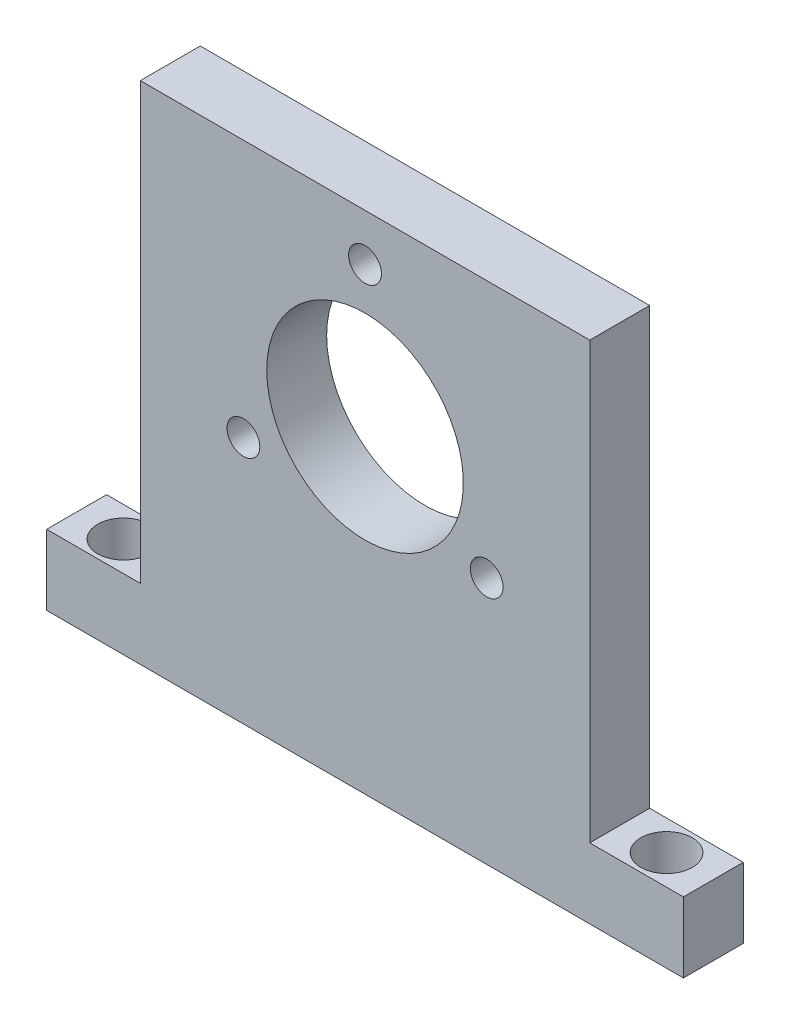
SolidWorks part; units mm, degrees
material "1060 Alloy"
ref_plane "Frontal Plane" through (0, 0, 0) normal (0, 0, 1) x (1, 0, 0)
ref_plane "Horizontal Plane" through (0, 0, 0) normal (0, 1, 0) x (1, 0, 0)
ref_plane "Profile Plane" through (0, 0, 0) normal (1, 0, 0) x (0, 0, -1)
sketch "Sketch2" plane through (0, 0, 0) normal (0, 0, 1) x (1, 0, 0)
  line L0 (-34, 0) -> (34, 0)
  line L1 (34, 0) -> (34, 7.5)
  line L2 (34, 7.5) -> (24, 7.5)
  line L3 (24, 7.5) -> (24, 54)
  line L4 (24, 54) -> (-24, 54)
  line L5 (-24, 54) -> (-24, 7.5)
  line L6 (-24, 7.5) -> (-34, 7.5)
  line L7 (-34, 7.5) -> (-34, 0)
  circle A0 centre (0, 34) radius 4.175
  point P4 (0, 0)
  point P11 (0, 54)
  dimension "D2" = 8.35
  dimension "D1" = 48
  dimension "D3" = 7.5
  dimension "D5" = 34
  dimension "D4" = 10
  dimension "D6" = 20
extrude "Boss-Extrude1" add sketch "Sketch2" against normal blind 6.4
ref_plane "Plane1" through (0, 0, -6.4) normal (0, 0, -1) x (-1, 0, 0)
sketch "Sketch3" plane through (0, 0, -6.4) normal (0, 0, -1) x (-1, 0, 0)
  circle A0 centre (0, 34) radius 10.5
  dimension "D1" = 21
extrude "Cut-Extrude1" cut sketch "Sketch3" against normal through all
sketch "Sketch4" plane through (0, 0, 0) normal (0, 0, 1) x (1, 0, 0)
  circle A0 centre (0, 34) radius 15 construction
  circle A1 centre (0, 34) radius 10.5 construction
  point P4 (0, 49)
  dimension "D1" = 30
hole_wizard "Ø3.5 (3.5) Diameter Hole1" positions "Sketch4" profile "Sketch5" hole size "Ø3.5" standard "ANSI Metric" end condition up to next
sketch "Sketch5" plane through (0, 49, 0) normal (1, 0, 0) x (0, -1, 0)
  line L0 (0, 0) -> (0, 6.4)
  line L1 (0, 6.4) -> (1.75, 6.4)
  line L2 (1.75, 6.4) -> (1.75, 0)
  line L5 (1.75, 0) -> (0, 0)
  line L11 (0, -6.35) -> (0, 107.95) construction
  dimension "Thru Hole Dia." = 3.5
  dimension "Thru Hole Depth" = 6.4
pattern_circular "CirPattern1" count 3 over 360 about axis through (0, 34, 0) along (0, 0, 1) of "Ø3.5 (3.5) Diameter Hole1"
sketch "Sketch12" plane through (0, 7.5, 0) normal (0, 1, 0) x (1, 0, 0)
  line L0 (-34, 6.4) -> (-34, 0) construction
  line L1 (-24, 6.4) -> (-24, 0) construction
  line L2 (24, 6.4) -> (24, 0) construction
  circle A0 centre (-29, 3.2) radius 2.75
  circle A1 centre (29, 3.2) radius 2.75
  point P7 (-34, 3.2)
  dimension "D1" = 5.5
  dimension "D2" = 5
  dimension "D3" = 5
extrude "Cut-Extrude2" cut sketch "Sketch12" along normal through all and the other way through all
equation "\"D1@Sketch2\"=\"EncoderRadius\"*2+1cm"
equation "\"D2@Sketch2\" = \"ActuatorPinD\" + 2mm"
equation "\"D3@Sketch2\"= \"EncoderHousingThickness\""
equation "\"D5@Sketch2\"=\"PillowBlockCenterH\""
equation "\"PinDiameter\"= 0"
equation "\"WallThickness\"= 0.5cm"
equation "\"BottomPlateX\"= 3ft"
equation "\"ActuatorL\"= 35cm"
equation "\"ActuatorPinD\"= 6.35mm"
equation "\"ActuatorPinL\"= 15cm"
equation "\"Box-X\"= 40cm"
equation "\"Box-Z\"= 20cm"
equation "\"Box-Y\"= 30cm"
equation "\"RotaryUnionThickness\"= 1cm"
equation "\"ArmPlateThickness\"= .125in"
equation "\"ArmPlateX\"= 18in"
equation "\"Arm1X\"= 5cm"
equation "\"Arm1L\"= 60cm"
equation "\"Arm2GAP\"= 5cm"
equation "\"Arm2L\"= 60cm"
equation "\"Arm2H\"= 5cm"
equation "\"Arm2Extension\"= 5cm"
equation "\"Arm3GAP\"= 5cm"
equation "\"Arm3L\"= 60cm"
equation "\"Arm3H\"= 5cm"
equation "\"Pin1-2L\"= \"Arm2GAP\" + (2 * \"WallThickness\")"
equation "\"Pin2-3L\"= \"Arm3GAP\" + (4 * \"WallThickness\")"
equation "\"DCMotor1D\"= 65mm"
equation "\"DCMotor1L\"= 215mm"
equation "\"DCMotor1ShaftL\"= 30mm"
equation "\"DCMotor2X\"= 68mm"
equation "\"DCMotor2D\"= 65mm"
equation "\"DCMotor2L\"= 208mm"
equation "\"DCMotor2ShaftL\"= 39mm"
equation "\"DCMotor2ShaftD\"= 15mm"
equation "\"BenchDepth\"= 5cm"
equation "\"BenchH\"= 10cm"
equation "\"BenchL\"= 15cm"
equation "\"PillowBlockW\"= 5cm"
equation "\"PillowBlockCenterH\"= \"DCMotor2X\"/2"
equation "\"EncoderRadius\"= 19mm"
equation "\"EncoderShaftL\"= 15mm"
equation "\"EncoderL\"= 33mm"
equation "\"EncoderHousingThickness\"= 7.5mm"
equation "\"PillowBlockCenterH\"= \"EncoderRadius\" + 5mm"
equation "\"RodRadius\"= .5cm"
equation "\"RodL\"= 20cm"
equation "\"PendulumShaftRadius\"= 4mm"
equation "\"PendulumShaftL\"= \"SlidePlateW\""
equation "\"EncoderShaftRadius\"= 3mm"
equation "\"BeltLockH\"= \"PulleyH\" + 11.885mm - (\"SlidePlateThickness\" + \"SlidePlateClearance\" + 15mm + 5mm)"
equation "\"BeltW\"= .375in"
equation "\"BeltThickness\"= 2mm"
equation "\"BeltL\"= 1500mm + \"BoxX\""
equation "\"HeadstoneThickness\"= 7.5mm"
equation "\"MotorShaftL\"= 18mm"
equation "\"MotorShaftRadius\"= 2.5mm"
equation "\"MotorRadius\"= 21mm"
equation "\"MotorL\"= 83mm"
equation "\"PulleyShaft2L\"= \"BoxX\"+ 3mm"
equation "\"PulleyShaftL\"= \"BoxX\" + 5cm"
equation "\"PulleyShaftDiameter\"= 8mm"
equation "\"PulleyH\"= 2cm + \"SlidePlateClearance\" + (\"SlidePlateThickness\"/2)"
equation "\"PulleyRadius\"= 15.1mm"
equation "\"BoxH\"= 2cm + \"SlidePlateClearance\" + \"SlidePlateThickness\" + 3cm"
equation "\"BoxX\"= \"RailGap\" + 30mm"
equation "\"BoxThickness\"= .5cm"
equation "\"SlidePlateClearance\"= 1cm"
equation "\"SlidePlateThickness\"= 3mm"
equation "\"SlidePlateW\"= 14cm"
equation "\"SlidePlateL\"= 14cm"
equation "\"RailGap\"= 5cm"
equation "\"BaseThickness\"= 1cm"
equation "\"BaseW\"= 30cm"
equation "\"BaseL\"= 1700mm"
